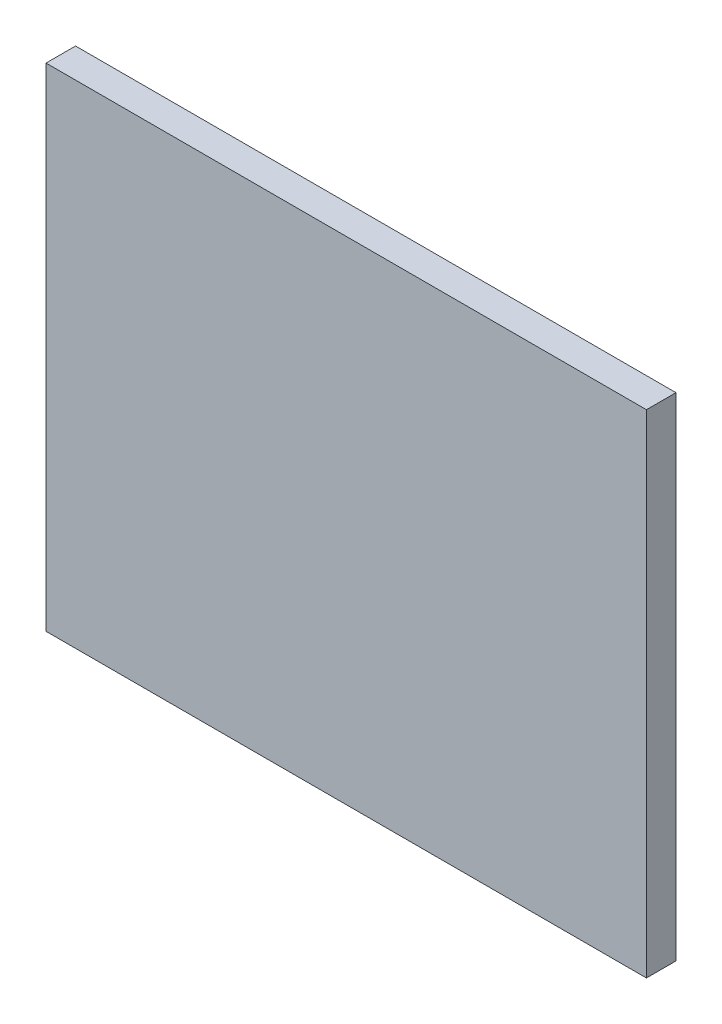
SolidWorks part; units mm, degrees
ref_plane "Front Plane" through (0, 0, 0) normal (0, 0, 1) x (1, 0, 0)
ref_plane "Top Plane" through (0, 0, 0) normal (0, 1, 0) x (1, 0, 0)
ref_plane "Right Plane" through (0, 0, 0) normal (1, 0, 0) x (0, 0, -1)
sketch "Sketch1" plane through (0, 0, 0) normal (0, 0, 1) x (1, 0, 0)
  line L1 (-30.5, 25) -> (30.5, 25)
  line L2 (-30.5, 25) -> (-30.5, -25)
  line L3 (-30.5, -25) -> (30.5, -25)
  line L4 (30.5, 25) -> (30.5, -25)
  line L5 (0, -25) -> (0, 25) construction
  line L6 (-30.5, 0) -> (30.5, 0) construction
  point P0 (0, 0)
  dimension "D1" = 61
  dimension "D2" = 50
extrude "Boss-Extrude1" add sketch "Sketch1" along normal blind 3
